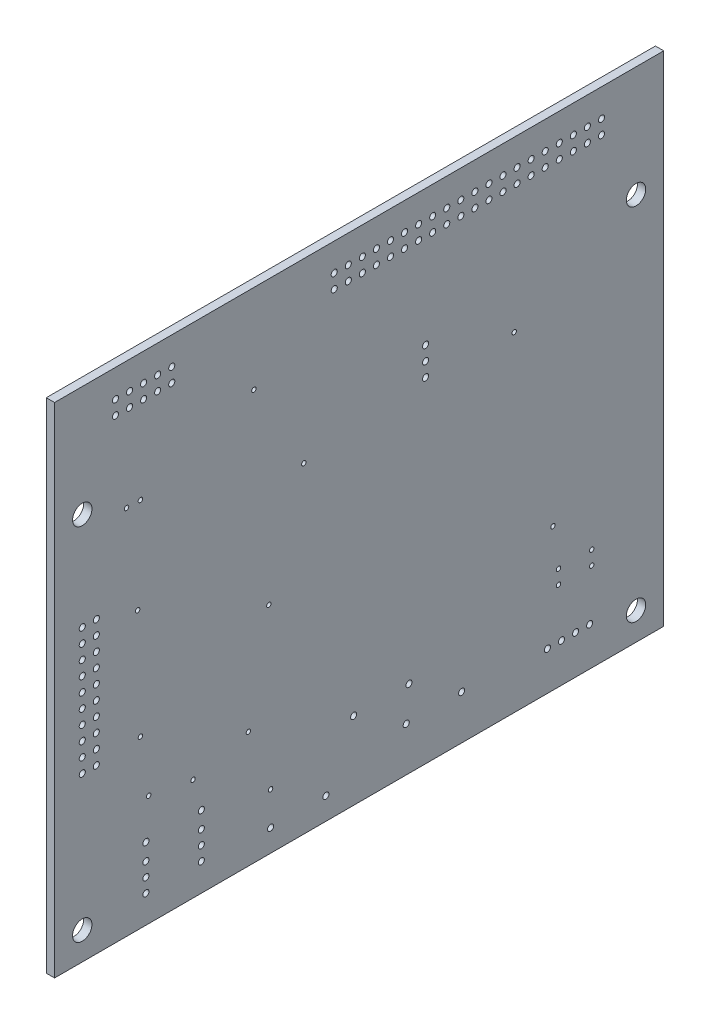
SolidWorks part; units mm, degrees
ref_plane "Спереди" through (0, 0, 0) normal (0, 0, 1) x (1, 0, 0)
ref_plane "Сверху" through (0, 0, 0) normal (0, 1, 0) x (1, 0, 0)
ref_plane "Справа" through (0, 0, 0) normal (1, 0, 0) x (0, 0, -1)
sketch "Эскиз1" plane through (0, 0, 0) normal (1, 0, 0) x (0, 0, -1)
  line L0 (-25.6582, 0) -> (27.1184, 0) construction
  line L2 (-75, -45) -> (35, -45)
  line L3 (-75, -45) -> (-75, 45)
  line L4 (-75, 45) -> (35, 45)
  line L5 (35, -45) -> (35, 45)
  circle A0 centre (-70, 25) radius 1.75
  circle A1 centre (-70, -40) radius 1.75
  circle A2 centre (30, -40) radius 1.75
  circle A3 centre (30, 25) radius 1.75
  dimension "D3" = 5
  dimension "D5" = 100
  dimension "D6" = 5
  dimension "D7" = 3.5
  dimension "D4" = 100
  dimension "D8" = 5
  dimension "D10" = 3.5
  dimension "D11" = 3.5
  dimension "D1" = 110
  dimension "D2" = 90
  dimension "D9" = 70
extrude "Вытянуть1" add sketch "Эскиз1" along normal blind 1.5
sketch "Эскиз2" plane through (1.5, 0, 0) normal (1, 0, 0) x (0, 0, -1)
  line L0 (-75, 45) -> (-75, -45) construction
  line L1 (-75, -45) -> (35, -45) construction
  line L2 (-8, 15.42) -> (-8, 29.336) construction
  circle A0 centre (-70, 7.335) radius 0.55
  circle A1 centre (-67.46, 7.335) radius 0.55
  circle A2 centre (-70, 4.795) radius 0.55
  circle A3 centre (-67.46, 4.795) radius 0.55
  circle A4 centre (-70, 2.255) radius 0.55
  circle A5 centre (-67.46, 2.255) radius 0.55
  circle A6 centre (-70, -0.285) radius 0.55
  circle A7 centre (-67.46, -0.285) radius 0.55
  circle A8 centre (-70, -2.825) radius 0.55
  circle A9 centre (-67.46, -2.825) radius 0.55
  circle A10 centre (-70, -5.365) radius 0.55
  circle A11 centre (-67.46, -5.365) radius 0.55
  circle A12 centre (-70, -7.905) radius 0.55
  circle A13 centre (-67.46, -7.905) radius 0.55
  circle A14 centre (-70, -10.445) radius 0.55
  circle A15 centre (-67.46, -10.445) radius 0.55
  circle A16 centre (-70, -12.985) radius 0.55
  circle A17 centre (-67.46, -12.985) radius 0.55
  circle A18 centre (-70, -15.525) radius 0.55
  circle A19 centre (-67.46, -15.525) radius 0.55
  circle A20 centre (-64, 40) radius 0.55
  circle A21 centre (-64, 37.46) radius 0.55
  circle A22 centre (-61.46, 40) radius 0.55
  circle A23 centre (-61.46, 37.46) radius 0.55
  circle A24 centre (-58.92, 40) radius 0.55
  circle A25 centre (-58.92, 37.46) radius 0.55
  circle A26 centre (-56.38, 40) radius 0.55
  circle A27 centre (-56.38, 37.46) radius 0.55
  circle A28 centre (-53.84, 40) radius 0.55
  circle A29 centre (-53.84, 37.46) radius 0.55
  circle A30 centre (-24.5, 40) radius 0.55
  circle A31 centre (-24.5, 37.46) radius 0.55
  circle A32 centre (-21.96, 40) radius 0.55
  circle A33 centre (-21.96, 37.46) radius 0.55
  circle A34 centre (-19.42, 40) radius 0.55
  circle A35 centre (-19.42, 37.46) radius 0.55
  circle A36 centre (-16.88, 40) radius 0.55
  circle A37 centre (-16.88, 37.46) radius 0.55
  circle A38 centre (-14.34, 40) radius 0.55
  circle A39 centre (-14.34, 37.46) radius 0.55
  circle A40 centre (-11.8, 40) radius 0.55
  circle A41 centre (-11.8, 37.46) radius 0.55
  circle A42 centre (-9.26, 40) radius 0.55
  circle A43 centre (-9.26, 37.46) radius 0.55
  circle A44 centre (-6.72, 40) radius 0.55
  circle A45 centre (-6.72, 37.46) radius 0.55
  circle A46 centre (-4.18, 40) radius 0.55
  circle A47 centre (-4.18, 37.46) radius 0.55
  circle A48 centre (-1.64, 40) radius 0.55
  circle A49 centre (-1.64, 37.46) radius 0.55
  circle A50 centre (0.9, 40) radius 0.55
  circle A51 centre (0.9, 37.46) radius 0.55
  circle A52 centre (3.44, 40) radius 0.55
  circle A53 centre (3.44, 37.46) radius 0.55
  circle A54 centre (5.98, 40) radius 0.55
  circle A55 centre (5.98, 37.46) radius 0.55
  circle A56 centre (8.52, 40) radius 0.55
  circle A57 centre (8.52, 37.46) radius 0.55
  circle A58 centre (11.06, 40) radius 0.55
  circle A59 centre (11.06, 37.46) radius 0.55
  circle A60 centre (13.6, 40) radius 0.55
  circle A61 centre (13.6, 37.46) radius 0.55
  circle A62 centre (16.14, 40) radius 0.55
  circle A63 centre (16.14, 37.46) radius 0.55
  circle A64 centre (18.68, 40) radius 0.55
  circle A65 centre (18.68, 37.46) radius 0.55
  circle A66 centre (21.22, 40) radius 0.55
  circle A67 centre (21.22, 37.46) radius 0.55
  circle A68 centre (23.76, 40) radius 0.55
  circle A69 centre (23.76, 37.46) radius 0.55
  circle A70 centre (-8, 20.5) radius 0.55
  circle A71 centre (-8, 17.96) radius 0.55
  circle A72 centre (-8, 15.42) radius 0.55
  circle A93 centre (50.03, -40.002) radius 0.55
  circle A94 centre (51.1804, -42.2666) radius 0.55
  circle A95 centre (52.3308, -44.5311) radius 0.55
  circle A96 centre (53.4812, -46.7957) radius 0.55
  dimension "D1" = 1.1
  dimension "D4" = 2.54
  dimension "D8" = 1.1
  dimension "D10" = 10.16
  dimension "D13" = 2.54
  dimension "D17" = 2.54
  dimension "D18" = 2.54
  dimension "D21" = 1.1
  dimension "D22" = 2.54
  dimension "D23" = 29.475
  dimension "D3" = 22.86
  dimension "D24" = 11
  dimension "D14" = 48.26
  dimension "D5" = 7.54
  dimension "D6" = 82.46
  dimension "D7" = 2.54
  dimension "D9" = 82.46
  dimension "D11" = 82.46
  dimension "D12" = 82.46
  dimension "D15" = 67
  dimension "D16" = 65.5
  dimension "D19" = 4.998
  dimension "D20" = 125.03
  dimension "D25" = 50.5
extrude "Вырез-Вытянуть1" cut sketch "Эскиз2" against normal blind 10
sketch "Эскиз4" plane through (1.5, 0, 0) normal (1, 0, 0) x (0, 0, -1)
  line L2 (14, -38) -> (10.517, -38) construction
  line L3 (-75, -45) -> (35, -45) construction
  line L4 (-75, 45) -> (-75, -45) construction
  circle A0 centre (14, -38) radius 0.55
  circle A1 centre (16.54, -38) radius 0.55
  circle A2 centre (19.08, -38) radius 0.55
  circle A3 centre (21.62, -38) radius 0.55
  dimension "D1" = 1.1
  dimension "D2" = 7
  dimension "D4" = 2.54
  dimension "D3" = 89
extrude "Вырез-Вытянуть3" cut sketch "Эскиз4" against normal blind 10
sketch "Эскиз5" plane through (1.5, 0, 0) normal (1, 0, 0) x (0, 0, -1)
  line L0 (-75, -45) -> (35, -45) construction
  line L1 (-75, 45) -> (-75, -45) construction
  line L2 (-62, 22) -> (-59.5, 22) construction
  line L3 (16, -29) -> (16, -26.5) construction
  line L4 (22, -29) -> (22, -26.5) construction
  circle A0 centre (15, -19.35) radius 0.4
  circle A1 centre (-30, 13) radius 0.4
  circle A2 centre (8, 14.5) radius 0.4
  circle A3 centre (-36, -35) radius 0.4
  circle A4 centre (-40, -24) radius 0.4
  circle A5 centre (-60, 5) radius 0.4
  circle A6 centre (-62, 22) radius 0.4
  circle A7 centre (-59.5, 22) radius 0.4
  circle A8 centre (16, -29) radius 0.4
  circle A9 centre (22, -29) radius 0.4
  circle A10 centre (22, -26.5) radius 0.4
  circle A11 centre (16, -26.5) radius 0.4
  circle A12 centre (-50, -26.5) radius 0.4
  dimension "D3" = 0.8
  dimension "D14" = 2.5
  dimension "D15" = 67
  dimension "D16" = 0.8
  dimension "D17" = 13
  dimension "D19" = 2.5
  dimension "D20" = 2.5
  dimension "D22" = 16
  dimension "D26" = 0.8
  dimension "D1" = 25.65
  dimension "D2" = 90
  dimension "D4" = 45
  dimension "D5" = 58
  dimension "D6" = 83
  dimension "D7" = 59.5
  dimension "D8" = 39
  dimension "D9" = 10
  dimension "D10" = 35
  dimension "D11" = 21
  dimension "D12" = 15
  dimension "D13" = 50
  dimension "D18" = 6
  dimension "D21" = 16
  dimension "D23" = 91
  dimension "D24" = 25
  dimension "D25" = 18.5
extrude "Вырез-Вытянуть4" cut sketch "Эскиз5" against normal blind 10
sketch "Эскиз6" plane through (1.5, 0, 0) normal (1, 0, 0) x (0, 0, -1)
  line L0 (-55.439, -40) -> (-33.7045, -40) construction
  line L1 (-75, -45) -> (35, -45) construction
  line L2 (-75, 45) -> (-75, -45) construction
  line L3 (-58.5, -40) -> (-58.5, -26.6217) construction
  line L4 (-58.5, -37.5) -> (-53.6305, -37.5) construction
  line L5 (-58.5, -35) -> (-52.91, -35) construction
  line L6 (-58.5, -32) -> (-53.3663, -32) construction
  line L7 (-48.5, -40) -> (-48.5, -30.1898) construction
  line L8 (-32.9887, -41) -> (-11.2543, -41) construction
  line L9 (-8.439, -37) -> (13.2955, -37) construction
  line L10 (-17.939, -31) -> (3.7955, -31) construction
  line L11 (-75, -45) -> (35, -45) construction
  circle A0 centre (-58.5, -40) radius 0.55
  circle A1 centre (-48.5, -40) radius 0.55
  circle A2 centre (14, -38) radius 0.55 construction
  circle A3 centre (-58.5, -37.5) radius 0.55
  circle A4 centre (-48.5, -37.5) radius 0.55
  circle A5 centre (-58.5, -35) radius 0.55
  circle A6 centre (-48.5, -35) radius 0.55
  circle A7 centre (-58.5, -32) radius 0.55
  circle A8 centre (-48.5, -32) radius 0.55
  circle A9 centre (-36, -41) radius 0.55
  circle A10 centre (-26, -41) radius 0.55
  circle A11 centre (-11.5, -37) radius 0.55
  circle A12 centre (-1.5, -37) radius 0.55
  circle A13 centre (-21, -31) radius 0.55
  circle A14 centre (-11, -31) radius 0.55
  circle A15 centre (-39, 29) radius 0.4
  circle A16 centre (-58, -25) radius 0.4
  circle A17 centre (-59.5, -15) radius 0.4
  dimension "D1" = 10
  dimension "D4" = 2.5
  dimension "D5" = 2.5
  dimension "D6" = 3
  dimension "D9" = 10
  dimension "D10" = 10
  dimension "D11" = 10
  dimension "D16" = 0.8
  dimension "D2" = 5
  dimension "D3" = 16.5
  dimension "D7" = 4
  dimension "D8" = 39
  dimension "D12" = 63.5
  dimension "D13" = 8
  dimension "D14" = 54
  dimension "D15" = 14
  dimension "D17" = 36
  dimension "D18" = 74
  dimension "D19" = 15.5
  dimension "D20" = 30
  dimension "D21" = 17
  dimension "D22" = 20
extrude "Вырез-Вытянуть5" cut sketch "Эскиз6" against normal blind 10
sketch "Эскиз7" plane through (1.5, 0, 0) normal (1, 0, 0) x (0, 0, -1)
  line L0 (-75, 45) -> (-75, -45) construction
  line L1 (-75, -45) -> (35, -45) construction
  circle A0 centre (-36.3, -6) radius 0.4
  dimension "D1" = 0.8
  dimension "D3" = 39
  dimension "D2" = 38.7
extrude "Вырез-Вытянуть6" cut sketch "Эскиз7" against normal blind 10
